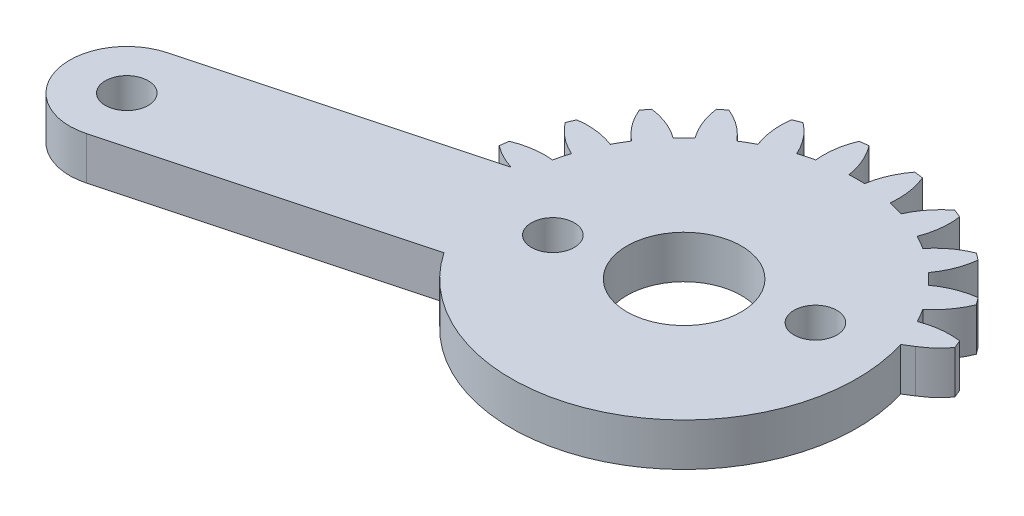
SolidWorks part; units mm, degrees
ref_plane "Front Plane" through (0, 0, 0) normal (0, 0, 1) x (1, 0, 0)
ref_plane "Top Plane" through (0, 0, 0) normal (0, 1, 0) x (1, 0, 0)
ref_plane "Right Plane" through (0, 0, 0) normal (1, 0, 0) x (0, 0, -1)
sketch "Sketch1" plane through (0, 0, 0) normal (0, 1, 0) x (1, 0, 0)
  line L0 (20.6437, 4) -> (2.0816, 4)
  line L1 (2.0816, -4) -> (20.6437, -4)
  arc A0 (2.0816, 4) -> (3.5217, 5.3071) centre (-0.7683, 8.5867) ccw
  arc A1 (3.5217, 5.3071) -> (3.2829, 5.8838) centre (-10.1063, 0) ccw
  arc A2 (3.2829, 5.8838) -> (0.6271, 5.5703) centre (2.5684, 0.5313) ccw
  arc A3 (0.6271, 5.5703) -> (0.0844, 6.5103) centre (-10.1063, 0) ccw
  arc A4 (0.0844, 6.5103) -> (1.6838, 8.6535) centre (-3.3089, 10.711) ccw
  arc A5 (1.6838, 8.6535) -> (1.3038, 9.1487) centre (-10.1063, 0) ccw
  arc A6 (1.3038, 9.1487) -> (-1.1803, 8.1585) centre (1.999, 3.7936) ccw
  arc A7 (-1.1803, 8.1585) -> (-1.9479, 8.926) centre (-10.1063, 0) ccw
  arc A8 (-1.9479, 8.926) -> (-0.9576, 11.4102) centre (-6.3127, 12.1053) ccw
  arc A9 (-0.9576, 11.4102) -> (-1.4528, 11.7901) centre (-10.1063, 0) ccw
  arc A10 (-1.4528, 11.7901) -> (-3.596, 10.1907) centre (0.6046, 6.7975) ccw
  arc A11 (-3.596, 10.1907) -> (-4.5361, 10.7334) centre (-10.1063, 0) ccw
  arc A12 (-4.5361, 10.7334) -> (-4.2225, 13.3892) centre (-9.5751, 12.6747) ccw
  arc A13 (-4.2225, 13.3892) -> (-4.7992, 13.6281) centre (-10.1063, 0) ccw
  arc A14 (-4.7992, 13.6281) -> (-6.4554, 11.5285) centre (-1.5196, 9.3381) ccw
  arc A15 (-6.4554, 11.5285) -> (-7.5039, 11.8094) centre (-10.1063, 0) ccw
  arc A16 (-7.5039, 11.8094) -> (-7.8884, 14.4558) centre (-12.8736, 12.3803) ccw
  arc A17 (-7.8884, 14.4558) -> (-8.5072, 14.5373) centre (-10.1063, 0) ccw
  arc A18 (-8.5072, 14.5373) -> (-9.5636, 12.0806) centre (-4.2291, 11.2423) ccw
  arc A19 (-9.5636, 12.0806) -> (-10.6491, 12.0806) centre (-10.1063, 0) ccw
  arc A20 (-10.6491, 12.0806) -> (-11.7054, 14.5373) centre (-15.9836, 11.2423) ccw
  arc A21 (-11.7054, 14.5373) -> (-12.3243, 14.4558) centre (-10.1063, 0) ccw
  arc A22 (-12.3243, 14.4558) -> (-12.7088, 11.8094) centre (-7.3391, 12.3803) ccw
  arc A23 (-12.7088, 11.8094) -> (-13.7573, 11.5285) centre (-10.1063, 0) ccw
  arc A24 (-13.7573, 11.5285) -> (-15.4135, 13.6281) centre (-18.6931, 9.3381) ccw
  arc A25 (-15.4135, 13.6281) -> (-15.9901, 13.3892) centre (-10.1063, 0) ccw
  arc A26 (-15.9901, 13.3892) -> (-15.6766, 10.7334) centre (-10.6376, 12.6747) ccw
  arc A27 (-15.6766, 10.7334) -> (-16.6166, 10.1907) centre (-10.1063, 0) ccw
  arc A28 (-16.6166, 10.1907) -> (-18.7599, 11.7901) centre (-20.8173, 6.7975) ccw
  arc A29 (-18.7599, 11.7901) -> (-19.255, 11.4102) centre (-10.1063, 0) ccw
  arc A30 (-19.255, 11.4102) -> (-18.2648, 8.926) centre (-13.9, 12.1053) ccw
  arc A31 (-18.2648, 8.926) -> (-19.0324, 8.1585) centre (-10.1063, 0) ccw
  arc A32 (-19.0324, 8.1585) -> (-21.5165, 9.1487) centre (-22.2117, 3.7936) ccw
  arc A33 (-21.5165, 9.1487) -> (-21.8965, 8.6535) centre (-10.1063, 0) ccw
  arc A34 (-21.8965, 8.6535) -> (-20.2971, 6.5103) centre (-16.9038, 10.711) ccw
  arc A35 (-20.2971, 6.5103) -> (-20.8398, 5.5703) centre (-10.1063, 0) ccw
  arc A36 (-20.8398, 5.5703) -> (-23.4956, 5.8838) centre (-22.7811, 0.5313) ccw
  arc A37 (-23.4956, 5.8838) -> (-23.7344, 5.3071) centre (-10.1063, 0) ccw
  arc A38 (-23.7344, 5.3071) -> (-21.6348, 3.6509) centre (-19.4444, 8.5867) ccw
  arc A39 (-21.6348, 3.6509) -> (-21.9157, 2.6025) centre (-10.1063, 0) ccw
  arc A40 (-21.9157, 2.6025) -> (-24.5622, 2.2179) centre (-22.4867, -2.7673) ccw
  arc A41 (-24.5622, 2.2179) -> (-24.6437, 1.5991) centre (-10.1063, 0) ccw
  arc A42 (-24.6437, 1.5991) -> (-22.1869, 0.5427) centre (-21.3486, 5.8773) ccw
  arc A43 (-22.1869, 0.5427) -> (-22.1869, -0.5427) centre (-10.1063, 0) ccw
  arc A44 (-22.1869, -0.5427) -> (-24.6437, -1.5991) centre (-21.3486, -5.8773) ccw
  arc A45 (-24.6437, -1.5991) -> (-24.5622, -2.2179) centre (-10.1063, 0) ccw
  arc A46 (-24.5622, -2.2179) -> (-21.9157, -2.6025) centre (-22.4867, 2.7673) ccw
  arc A47 (-21.9157, -2.6025) -> (-21.6348, -3.6509) centre (-10.1063, 0) ccw
  arc A48 (-21.6348, -3.6509) -> (-23.7344, -5.3071) centre (-19.4444, -8.5867) ccw
  arc A49 (-23.7344, -5.3071) -> (-23.4956, -5.8838) centre (-10.1063, 0) ccw
  arc A50 (-23.4956, -5.8838) -> (-20.8398, -5.5703) centre (-22.7811, -0.5313) ccw
  arc A51 (-20.8398, -5.5703) -> (-20.2971, -6.5103) centre (-10.1063, 0) ccw
  arc A52 (-20.2971, -6.5103) -> (-21.8965, -8.6535) centre (-16.9038, -10.711) ccw
  arc A53 (-21.8965, -8.6535) -> (-21.5165, -9.1487) centre (-10.1063, 0) ccw
  arc A54 (-21.5165, -9.1487) -> (-19.0324, -8.1585) centre (-22.2117, -3.7936) ccw
  arc A55 (-19.0324, -8.1585) -> (-18.2648, -8.926) centre (-10.1063, 0) ccw
  arc A56 (-18.2648, -8.926) -> (-19.255, -11.4102) centre (-13.9, -12.1053) ccw
  arc A57 (-19.255, -11.4102) -> (-18.7599, -11.7901) centre (-10.1063, 0) ccw
  arc A58 (-18.7599, -11.7901) -> (-16.6166, -10.1907) centre (-20.8173, -6.7975) ccw
  arc A59 (-16.6166, -10.1907) -> (-15.6766, -10.7334) centre (-10.1063, 0) ccw
  arc A60 (-15.6766, -10.7334) -> (-15.9901, -13.3892) centre (-10.6376, -12.6747) ccw
  arc A61 (-15.9901, -13.3892) -> (-15.4135, -13.6281) centre (-10.1063, 0) ccw
  arc A62 (-15.4135, -13.6281) -> (-13.7573, -11.5285) centre (-18.6931, -9.3381) ccw
  arc A63 (-13.7573, -11.5285) -> (-12.7088, -11.8094) centre (-10.1063, 0) ccw
  arc A64 (-12.7088, -11.8094) -> (-12.3243, -14.4558) centre (-7.3391, -12.3803) ccw
  arc A65 (-12.3243, -14.4558) -> (-11.7054, -14.5373) centre (-10.1063, 0) ccw
  arc A66 (-11.7054, -14.5373) -> (-10.6491, -12.0806) centre (-15.9836, -11.2423) ccw
  arc A67 (-10.6491, -12.0806) -> (-9.5636, -12.0806) centre (-10.1063, 0) ccw
  arc A68 (-9.5636, -12.0806) -> (-8.5072, -14.5373) centre (-4.2291, -11.2423) ccw
  arc A69 (-8.5072, -14.5373) -> (-7.8884, -14.4558) centre (-10.1063, 0) ccw
  arc A70 (-7.8884, -14.4558) -> (-7.5039, -11.8094) centre (-12.8736, -12.3803) ccw
  arc A71 (-7.5039, -11.8094) -> (-6.4554, -11.5285) centre (-10.1063, 0) ccw
  arc A72 (-6.4554, -11.5285) -> (-4.7992, -13.6281) centre (-1.5196, -9.3381) ccw
  arc A73 (-4.7992, -13.6281) -> (-4.2225, -13.3892) centre (-10.1063, 0) ccw
  arc A74 (-4.2225, -13.3892) -> (-4.5361, -10.7334) centre (-9.5751, -12.6747) ccw
  arc A75 (-4.5361, -10.7334) -> (-3.596, -10.1907) centre (-10.1063, 0) ccw
  arc A76 (-3.596, -10.1907) -> (-1.4528, -11.7901) centre (0.6046, -6.7975) ccw
  arc A77 (-1.4528, -11.7901) -> (-0.9576, -11.4102) centre (-10.1063, 0) ccw
  arc A78 (-0.9576, -11.4102) -> (-1.9479, -8.926) centre (-6.3127, -12.1053) ccw
  arc A79 (-1.9479, -8.926) -> (-1.1803, -8.1585) centre (-10.1063, 0) ccw
  arc A80 (-1.1803, -8.1585) -> (1.3038, -9.1487) centre (1.999, -3.7936) ccw
  arc A81 (1.3038, -9.1487) -> (1.6838, -8.6535) centre (-10.1063, 0) ccw
  arc A82 (1.6838, -8.6535) -> (0.0844, -6.5103) centre (-3.3089, -10.711) ccw
  arc A83 (0.0844, -6.5103) -> (0.6271, -5.5703) centre (-10.1063, 0) ccw
  arc A84 (0.6271, -5.5703) -> (3.2829, -5.8838) centre (2.5684, -0.5313) ccw
  arc A85 (3.2829, -5.8838) -> (3.5217, -5.3071) centre (-10.1063, 0) ccw
  arc A86 (3.5217, -5.3071) -> (2.0816, -4) centre (-0.7683, -8.5867) ccw
  arc A87 (20.6437, -4) -> (20.6437, 4) centre (20.6437, 0) ccw
  circle A88 centre (-10.1063, 0) radius 1.5
  circle A89 centre (20.6437, 0) radius 1.5
  dimension "D1" = 3
  dimension "D2" = 3
extrude "Boss-Extrude1" add sketch "Sketch1" along normal blind 3
sketch "Sketch3" plane through (0, 3, 0) normal (0, 1, 0) x (1, 0, 0)
  line L0 (-10.1063, 0) -> (-40.8563, 0) construction
  line L1 (-10.1063, 0) -> (-40.8563, -8.2394)
  line L2 (-11.1416, 3.8637) -> (-41.8916, -4.3757)
  line L3 (-9.0711, -3.8637) -> (-39.8211, -12.1031)
  circle A0 centre (-10.1063, 0) radius 1.5
  circle A1 centre (20.6437, 0) radius 1.5 construction
  circle A2 centre (20.6437, 0) radius 1.5
  circle A3 centre (-40.8563, -8.2394) radius 1.5
  circle A4 centre (-40.8563, -8.2394) radius 4
  circle A5 centre (-10.1063, 0) radius 4
  dimension "D2" = 3
  dimension "D5" = 3
  dimension "D6" = 8
  dimension "D7" = 8
  dimension "D1" = 30.75
  dimension "D3" = 30.75
  dimension "D4" = 15
extrude "Boss-Extrude2" add sketch "Sketch3" against normal blind 3
sketch "Sketch4" plane through (0, 3, 0) normal (0, 1, 0) x (1, 0, 0)
  line L0 (20.6437, 4) -> (2.0816, 4) construction
  line L1 (2.0816, -4) -> (20.6437, -4) construction
  line L2 (20.6437, 4) -> (2.0816, 4)
  line L3 (2.0816, -4) -> (20.6437, -4)
  line L4 (2.0816, 4) -> (1.4381, 3.6001)
  line L5 (-20.8438, -7.0182) -> (-20.0942, -6.8174)
  line L8 (-22.9143, 0.7092) -> (-41.8916, -4.3757)
  line L9 (-39.8211, -12.1031) -> (-20.8438, -7.0182)
  line L10 (2.0816, -4) -> (20.6437, -4)
  line L11 (20.6437, 4) -> (2.0816, 4)
  line L12 (-22.9143, 0.7092) -> (-41.8916, -4.3757)
  line L13 (-39.8211, -12.1031) -> (-20.8438, -7.0182)
  line L14 (2.0816, -4) -> (20.6437, -4)
  line L15 (20.6437, 4) -> (2.0816, 4)
  circle A0 centre (-10.1063, 0) radius 12.0927
  arc A1 (3.2829, 5.8838) -> (0.6271, 5.5703) centre (2.5684, 0.5313) ccw construction
  arc A2 (3.5217, 5.3071) -> (3.2829, 5.8838) centre (-10.1063, 0) ccw construction
  arc A3 (2.0816, 4) -> (3.5217, 5.3071) centre (-0.7683, 8.5867) ccw construction
  arc A4 (20.6437, -4) -> (20.6437, 4) centre (20.6437, 0) ccw construction
  arc A5 (3.5217, -5.3071) -> (2.0816, -4) centre (-0.7683, -8.5867) ccw construction
  arc A6 (3.2829, -5.8838) -> (3.5217, -5.3071) centre (-10.1063, 0) ccw construction
  arc A7 (0.6271, -5.5703) -> (3.2829, -5.8838) centre (2.5684, -0.5313) ccw construction
  arc A8 (3.2829, 5.8838) -> (0.6271, 5.5703) centre (2.5684, 0.5313) ccw
  arc A9 (3.5217, 5.3071) -> (3.2829, 5.8838) centre (-10.1063, 0) ccw
  arc A10 (2.0816, 4) -> (3.5217, 5.3071) centre (-0.7683, 8.5867) ccw
  arc A11 (20.6437, -4) -> (20.6437, 4) centre (20.6437, 0) ccw
  arc A12 (3.5217, -5.3071) -> (2.0816, -4) centre (-0.7683, -8.5867) ccw
  arc A13 (3.2829, -5.8838) -> (3.5217, -5.3071) centre (-10.1063, 0) ccw
  arc A14 (0.6271, -5.5703) -> (3.2829, -5.8838) centre (2.5684, -0.5313) ccw
  arc A95 (-24.6437, 1.5991) -> (-22.9143, 0.7092) centre (-21.3486, 5.8773) ccw
  arc A96 (-41.8916, -4.3757) -> (-39.8211, -12.1031) centre (-40.8563, -8.2394) ccw
  arc A97 (-20.8438, -7.0182) -> (-21.8965, -8.6535) centre (-16.9038, -10.711) ccw
  arc A98 (-21.8965, -8.6535) -> (-21.5165, -9.1487) centre (-10.1063, 0) ccw
  arc A99 (-21.5165, -9.1487) -> (-19.0324, -8.1585) centre (-22.2117, -3.7936) ccw
  arc A100 (-19.0324, -8.1585) -> (-18.2648, -8.926) centre (-10.1063, 0) ccw
  arc A101 (-18.2648, -8.926) -> (-19.255, -11.4102) centre (-13.9, -12.1053) ccw
  arc A102 (-19.255, -11.4102) -> (-18.7599, -11.7901) centre (-10.1063, 0) ccw
  arc A103 (-18.7599, -11.7901) -> (-16.6166, -10.1907) centre (-20.8173, -6.7975) ccw
  arc A104 (-16.6166, -10.1907) -> (-15.6766, -10.7334) centre (-10.1063, 0) ccw
  arc A105 (-15.6766, -10.7334) -> (-15.9901, -13.3892) centre (-10.6376, -12.6747) ccw
  arc A106 (-15.9901, -13.3892) -> (-15.4135, -13.6281) centre (-10.1063, 0) ccw
  arc A107 (-15.4135, -13.6281) -> (-13.7573, -11.5285) centre (-18.6931, -9.3381) ccw
  arc A108 (-13.7573, -11.5285) -> (-12.7088, -11.8094) centre (-10.1063, 0) ccw
  arc A109 (-12.7088, -11.8094) -> (-12.3243, -14.4558) centre (-7.3391, -12.3803) ccw
  arc A110 (-12.3243, -14.4558) -> (-11.7054, -14.5373) centre (-10.1063, 0) ccw
  arc A111 (-11.7054, -14.5373) -> (-10.6491, -12.0806) centre (-15.9836, -11.2423) ccw
  arc A112 (-10.6491, -12.0806) -> (-9.5636, -12.0806) centre (-10.1063, 0) ccw
  arc A113 (-9.5636, -12.0806) -> (-8.5072, -14.5373) centre (-4.2291, -11.2423) ccw
  arc A114 (-8.5072, -14.5373) -> (-7.8884, -14.4558) centre (-10.1063, 0) ccw
  arc A115 (-7.8884, -14.4558) -> (-7.5039, -11.8094) centre (-12.8736, -12.3803) ccw
  arc A116 (-7.5039, -11.8094) -> (-6.4554, -11.5285) centre (-10.1063, 0) ccw
  arc A117 (-6.4554, -11.5285) -> (-4.7992, -13.6281) centre (-1.5196, -9.3381) ccw
  arc A118 (-4.7992, -13.6281) -> (-4.2225, -13.3892) centre (-10.1063, 0) ccw
  arc A119 (-4.2225, -13.3892) -> (-4.5361, -10.7334) centre (-9.5751, -12.6747) ccw
  arc A120 (-4.5361, -10.7334) -> (-3.596, -10.1907) centre (-10.1063, 0) ccw
  arc A121 (-3.596, -10.1907) -> (-1.4528, -11.7901) centre (0.6046, -6.7975) ccw
  arc A122 (-1.4528, -11.7901) -> (-0.9576, -11.4102) centre (-10.1063, 0) ccw
  arc A123 (-0.9576, -11.4102) -> (-1.9479, -8.926) centre (-6.3127, -12.1053) ccw
  arc A124 (-1.9479, -8.926) -> (-1.1803, -8.1585) centre (-10.1063, 0) ccw
  arc A125 (-1.1803, -8.1585) -> (1.3038, -9.1487) centre (1.999, -3.7936) ccw
  arc A126 (1.3038, -9.1487) -> (1.6838, -8.6535) centre (-10.1063, 0) ccw
  arc A127 (1.6838, -8.6535) -> (0.0844, -6.5103) centre (-3.3089, -10.711) ccw
  arc A128 (0.0844, -6.5103) -> (0.6271, -5.5703) centre (-10.1063, 0) ccw
  arc A129 (0.6271, -5.5703) -> (3.2829, -5.8838) centre (2.5684, -0.5313) ccw
  arc A130 (3.2829, -5.8838) -> (3.5217, -5.3071) centre (-10.1063, 0) ccw
  arc A131 (3.5217, -5.3071) -> (2.0816, -4) centre (-0.7683, -8.5867) ccw
  arc A132 (20.6437, -4) -> (20.6437, 4) centre (20.6437, 0) ccw
  arc A133 (2.0816, 4) -> (3.5217, 5.3071) centre (-0.7683, 8.5867) ccw
  arc A134 (3.5217, 5.3071) -> (3.2829, 5.8838) centre (-10.1063, 0) ccw
  arc A135 (3.2829, 5.8838) -> (0.6271, 5.5703) centre (2.5684, 0.5313) ccw
  arc A136 (0.6271, 5.5703) -> (0.0844, 6.5103) centre (-10.1063, 0) ccw
  arc A137 (0.0844, 6.5103) -> (1.6838, 8.6535) centre (-3.3089, 10.711) ccw
  arc A138 (1.6838, 8.6535) -> (1.3038, 9.1487) centre (-10.1063, 0) ccw
  arc A139 (1.3038, 9.1487) -> (-1.1803, 8.1585) centre (1.999, 3.7936) ccw
  arc A140 (-1.1803, 8.1585) -> (-1.9479, 8.926) centre (-10.1063, 0) ccw
  arc A141 (-1.9479, 8.926) -> (-0.9576, 11.4102) centre (-6.3127, 12.1053) ccw
  arc A142 (-0.9576, 11.4102) -> (-1.4528, 11.7901) centre (-10.1063, 0) ccw
  arc A143 (-1.4528, 11.7901) -> (-3.596, 10.1907) centre (0.6046, 6.7975) ccw
  arc A144 (-3.596, 10.1907) -> (-4.5361, 10.7334) centre (-10.1063, 0) ccw
  arc A145 (-4.5361, 10.7334) -> (-4.2225, 13.3892) centre (-9.5751, 12.6747) ccw
  arc A146 (-4.2225, 13.3892) -> (-4.7992, 13.6281) centre (-10.1063, 0) ccw
  arc A147 (-4.7992, 13.6281) -> (-6.4554, 11.5285) centre (-1.5196, 9.3381) ccw
  arc A148 (-6.4554, 11.5285) -> (-7.5039, 11.8094) centre (-10.1063, 0) ccw
  arc A149 (-7.5039, 11.8094) -> (-7.8884, 14.4558) centre (-12.8736, 12.3803) ccw
  arc A150 (-7.8884, 14.4558) -> (-8.5072, 14.5373) centre (-10.1063, 0) ccw
  arc A151 (-8.5072, 14.5373) -> (-9.5636, 12.0806) centre (-4.2291, 11.2423) ccw
  arc A152 (-9.5636, 12.0806) -> (-10.6491, 12.0806) centre (-10.1063, 0) ccw
  arc A153 (-10.6491, 12.0806) -> (-11.7054, 14.5373) centre (-15.9836, 11.2423) ccw
  arc A154 (-11.7054, 14.5373) -> (-12.3243, 14.4558) centre (-10.1063, 0) ccw
  arc A155 (-12.3243, 14.4558) -> (-12.7088, 11.8094) centre (-7.3391, 12.3803) ccw
  arc A156 (-12.7088, 11.8094) -> (-13.7573, 11.5285) centre (-10.1063, 0) ccw
  arc A157 (-13.7573, 11.5285) -> (-15.4135, 13.6281) centre (-18.6931, 9.3381) ccw
  arc A158 (-15.4135, 13.6281) -> (-15.9901, 13.3892) centre (-10.1063, 0) ccw
  arc A159 (-15.9901, 13.3892) -> (-15.6766, 10.7334) centre (-10.6376, 12.6747) ccw
  arc A160 (-15.6766, 10.7334) -> (-16.6166, 10.1907) centre (-10.1063, 0) ccw
  arc A161 (-16.6166, 10.1907) -> (-18.7599, 11.7901) centre (-20.8173, 6.7975) ccw
  arc A162 (-18.7599, 11.7901) -> (-19.255, 11.4102) centre (-10.1063, 0) ccw
  arc A163 (-19.255, 11.4102) -> (-18.2648, 8.926) centre (-13.9, 12.1053) ccw
  arc A164 (-18.2648, 8.926) -> (-19.0324, 8.1585) centre (-10.1063, 0) ccw
  arc A165 (-19.0324, 8.1585) -> (-21.5165, 9.1487) centre (-22.2117, 3.7936) ccw
  arc A166 (-21.5165, 9.1487) -> (-21.8965, 8.6535) centre (-10.1063, 0) ccw
  arc A167 (-21.8965, 8.6535) -> (-20.2971, 6.5103) centre (-16.9038, 10.711) ccw
  arc A168 (-20.2971, 6.5103) -> (-20.8398, 5.5703) centre (-10.1063, 0) ccw
  arc A169 (-20.8398, 5.5703) -> (-23.4956, 5.8838) centre (-22.7811, 0.5313) ccw
  arc A170 (-23.4956, 5.8838) -> (-23.7344, 5.3071) centre (-10.1063, 0) ccw
  arc A171 (-23.7344, 5.3071) -> (-21.6348, 3.6509) centre (-19.4444, 8.5867) ccw
  arc A172 (-21.6348, 3.6509) -> (-21.9157, 2.6025) centre (-10.1063, 0) ccw
  arc A173 (-21.9157, 2.6025) -> (-24.5622, 2.2179) centre (-22.4867, -2.7673) ccw
  arc A174 (-24.5622, 2.2179) -> (-24.6437, 1.5991) centre (-10.1063, 0) ccw
  arc A175 (-24.6437, 1.5991) -> (-22.9143, 0.7092) centre (-21.3486, 5.8773) ccw
  arc A176 (-41.8916, -4.3757) -> (-39.8211, -12.1031) centre (-40.8563, -8.2394) ccw
  arc A177 (-20.8438, -7.0182) -> (-21.8965, -8.6535) centre (-16.9038, -10.711) ccw
  arc A178 (-21.8965, -8.6535) -> (-21.5165, -9.1487) centre (-10.1063, 0) ccw
  arc A179 (-21.5165, -9.1487) -> (-19.0324, -8.1585) centre (-22.2117, -3.7936) ccw
  arc A180 (-19.0324, -8.1585) -> (-18.2648, -8.926) centre (-10.1063, 0) ccw
  arc A181 (-18.2648, -8.926) -> (-19.255, -11.4102) centre (-13.9, -12.1053) ccw
  arc A182 (-19.255, -11.4102) -> (-18.7599, -11.7901) centre (-10.1063, 0) ccw
  arc A183 (-18.7599, -11.7901) -> (-16.6166, -10.1907) centre (-20.8173, -6.7975) ccw
  arc A184 (-16.6166, -10.1907) -> (-15.6766, -10.7334) centre (-10.1063, 0) ccw
  arc A185 (-15.6766, -10.7334) -> (-15.9901, -13.3892) centre (-10.6376, -12.6747) ccw
  arc A186 (-15.9901, -13.3892) -> (-15.4135, -13.6281) centre (-10.1063, 0) ccw
  arc A187 (-15.4135, -13.6281) -> (-13.7573, -11.5285) centre (-18.6931, -9.3381) ccw
  arc A188 (-13.7573, -11.5285) -> (-12.7088, -11.8094) centre (-10.1063, 0) ccw
  arc A189 (-12.7088, -11.8094) -> (-12.3243, -14.4558) centre (-7.3391, -12.3803) ccw
  arc A190 (-12.3243, -14.4558) -> (-11.7054, -14.5373) centre (-10.1063, 0) ccw
  arc A191 (-11.7054, -14.5373) -> (-10.6491, -12.0806) centre (-15.9836, -11.2423) ccw
  arc A192 (-10.6491, -12.0806) -> (-9.5636, -12.0806) centre (-10.1063, 0) ccw
  arc A193 (-9.5636, -12.0806) -> (-8.5072, -14.5373) centre (-4.2291, -11.2423) ccw
  arc A194 (-8.5072, -14.5373) -> (-7.8884, -14.4558) centre (-10.1063, 0) ccw
  arc A195 (-7.8884, -14.4558) -> (-7.5039, -11.8094) centre (-12.8736, -12.3803) ccw
  arc A196 (-7.5039, -11.8094) -> (-6.4554, -11.5285) centre (-10.1063, 0) ccw
  arc A197 (-6.4554, -11.5285) -> (-4.7992, -13.6281) centre (-1.5196, -9.3381) ccw
  arc A198 (-4.7992, -13.6281) -> (-4.2225, -13.3892) centre (-10.1063, 0) ccw
  arc A199 (-4.2225, -13.3892) -> (-4.5361, -10.7334) centre (-9.5751, -12.6747) ccw
  arc A200 (-4.5361, -10.7334) -> (-3.596, -10.1907) centre (-10.1063, 0) ccw
  arc A201 (-3.596, -10.1907) -> (-1.4528, -11.7901) centre (0.6046, -6.7975) ccw
  arc A202 (-1.4528, -11.7901) -> (-0.9576, -11.4102) centre (-10.1063, 0) ccw
  arc A203 (-0.9576, -11.4102) -> (-1.9479, -8.926) centre (-6.3127, -12.1053) ccw
  arc A204 (-1.9479, -8.926) -> (-1.1803, -8.1585) centre (-10.1063, 0) ccw
  arc A205 (-1.1803, -8.1585) -> (1.3038, -9.1487) centre (1.999, -3.7936) ccw
  arc A206 (1.3038, -9.1487) -> (1.6838, -8.6535) centre (-10.1063, 0) ccw
  arc A207 (1.6838, -8.6535) -> (0.0844, -6.5103) centre (-3.3089, -10.711) ccw
  arc A208 (0.0844, -6.5103) -> (0.6271, -5.5703) centre (-10.1063, 0) ccw
  arc A209 (0.6271, -5.5703) -> (3.2829, -5.8838) centre (2.5684, -0.5313) ccw
  arc A210 (3.2829, -5.8838) -> (3.5217, -5.3071) centre (-10.1063, 0) ccw
  arc A211 (3.5217, -5.3071) -> (2.0816, -4) centre (-0.7683, -8.5867) ccw
  arc A212 (20.6437, -4) -> (20.6437, 4) centre (20.6437, 0) ccw
  arc A213 (2.0816, 4) -> (3.5217, 5.3071) centre (-0.7683, 8.5867) ccw
  arc A214 (3.5217, 5.3071) -> (3.2829, 5.8838) centre (-10.1063, 0) ccw
  arc A215 (3.2829, 5.8838) -> (0.6271, 5.5703) centre (2.5684, 0.5313) ccw
  arc A216 (0.6271, 5.5703) -> (0.0844, 6.5103) centre (-10.1063, 0) ccw
  arc A217 (0.0844, 6.5103) -> (1.6838, 8.6535) centre (-3.3089, 10.711) ccw
  arc A218 (1.6838, 8.6535) -> (1.3038, 9.1487) centre (-10.1063, 0) ccw
  arc A219 (1.3038, 9.1487) -> (-1.1803, 8.1585) centre (1.999, 3.7936) ccw
  arc A220 (-1.1803, 8.1585) -> (-1.9479, 8.926) centre (-10.1063, 0) ccw
  arc A221 (-1.9479, 8.926) -> (-0.9576, 11.4102) centre (-6.3127, 12.1053) ccw
  arc A222 (-0.9576, 11.4102) -> (-1.4528, 11.7901) centre (-10.1063, 0) ccw
  arc A223 (-1.4528, 11.7901) -> (-3.596, 10.1907) centre (0.6046, 6.7975) ccw
  arc A224 (-3.596, 10.1907) -> (-4.5361, 10.7334) centre (-10.1063, 0) ccw
  arc A225 (-4.5361, 10.7334) -> (-4.2225, 13.3892) centre (-9.5751, 12.6747) ccw
  arc A226 (-4.2225, 13.3892) -> (-4.7992, 13.6281) centre (-10.1063, 0) ccw
  arc A227 (-4.7992, 13.6281) -> (-6.4554, 11.5285) centre (-1.5196, 9.3381) ccw
  arc A228 (-6.4554, 11.5285) -> (-7.5039, 11.8094) centre (-10.1063, 0) ccw
  arc A229 (-7.5039, 11.8094) -> (-7.8884, 14.4558) centre (-12.8736, 12.3803) ccw
  arc A230 (-7.8884, 14.4558) -> (-8.5072, 14.5373) centre (-10.1063, 0) ccw
  arc A231 (-8.5072, 14.5373) -> (-9.5636, 12.0806) centre (-4.2291, 11.2423) ccw
  arc A232 (-9.5636, 12.0806) -> (-10.6491, 12.0806) centre (-10.1063, 0) ccw
  arc A233 (-10.6491, 12.0806) -> (-11.7054, 14.5373) centre (-15.9836, 11.2423) ccw
  arc A234 (-11.7054, 14.5373) -> (-12.3243, 14.4558) centre (-10.1063, 0) ccw
  arc A235 (-12.3243, 14.4558) -> (-12.7088, 11.8094) centre (-7.3391, 12.3803) ccw
  arc A236 (-12.7088, 11.8094) -> (-13.7573, 11.5285) centre (-10.1063, 0) ccw
  arc A237 (-13.7573, 11.5285) -> (-15.4135, 13.6281) centre (-18.6931, 9.3381) ccw
  arc A238 (-15.4135, 13.6281) -> (-15.9901, 13.3892) centre (-10.1063, 0) ccw
  arc A239 (-15.9901, 13.3892) -> (-15.6766, 10.7334) centre (-10.6376, 12.6747) ccw
  arc A240 (-15.6766, 10.7334) -> (-16.6166, 10.1907) centre (-10.1063, 0) ccw
  arc A241 (-16.6166, 10.1907) -> (-18.7599, 11.7901) centre (-20.8173, 6.7975) ccw
  arc A242 (-18.7599, 11.7901) -> (-19.255, 11.4102) centre (-10.1063, 0) ccw
  arc A243 (-19.255, 11.4102) -> (-18.2648, 8.926) centre (-13.9, 12.1053) ccw
  arc A244 (-18.2648, 8.926) -> (-19.0324, 8.1585) centre (-10.1063, 0) ccw
  arc A245 (-19.0324, 8.1585) -> (-21.5165, 9.1487) centre (-22.2117, 3.7936) ccw
  arc A246 (-21.5165, 9.1487) -> (-21.8965, 8.6535) centre (-10.1063, 0) ccw
  arc A247 (-21.8965, 8.6535) -> (-20.2971, 6.5103) centre (-16.9038, 10.711) ccw
  arc A248 (-20.2971, 6.5103) -> (-20.8398, 5.5703) centre (-10.1063, 0) ccw
  arc A249 (-20.8398, 5.5703) -> (-23.4956, 5.8838) centre (-22.7811, 0.5313) ccw
  arc A250 (-23.4956, 5.8838) -> (-23.7344, 5.3071) centre (-10.1063, 0) ccw
  arc A251 (-23.7344, 5.3071) -> (-21.6348, 3.6509) centre (-19.4444, 8.5867) ccw
  arc A252 (-21.6348, 3.6509) -> (-21.9157, 2.6025) centre (-10.1063, 0) ccw
  arc A253 (-21.9157, 2.6025) -> (-24.5622, 2.2179) centre (-22.4867, -2.7673) ccw
  arc A254 (-24.5622, 2.2179) -> (-24.6437, 1.5991) centre (-10.1063, 0) ccw
  dimension "D2" = 24.1855
  dimension "D1" = 0
extrude "Cut-Extrude1" cut sketch "Sketch4" against normal blind 3 contours A178 A179 A0 L5 A177 | A182 A183 A0 A181 | A186 A187 A0 A185 | A190 A191 A0 A189 | A194 A195 A0 A193 | A198 A199 A0 A197 | A202 A203 A0 A201 | A206 A207 A0 A205 | A0 A14 A13 A12 L3 A11 L2 L4
sketch "Sketch5" plane through (0, 3, 0) normal (0, 1, 0) x (1, 0, 0)
  line L0 (-40.8563, -8.2394) -> (-10.1063, 0) construction
  line L1 (-10.1063, 0) -> (1.5744, 3.1298) construction
  arc A0 (-20.0942, -6.8174) -> (1.4381, 3.6001) centre (-10.1063, 0) ccw construction
  circle A1 centre (-10.1063, 0) radius 7.5 construction
  circle A2 centre (-2.8619, 1.9411) radius 1.5
  circle A3 centre (-17.3508, -1.9411) radius 1.5
  circle A4 centre (-10.1063, 0) radius 4
  dimension "D1" = 15
  dimension "D2" = 3
  dimension "D3" = 3
  dimension "D4" = 8
extrude "Cut-Extrude2" cut sketch "Sketch5" against normal up to next
